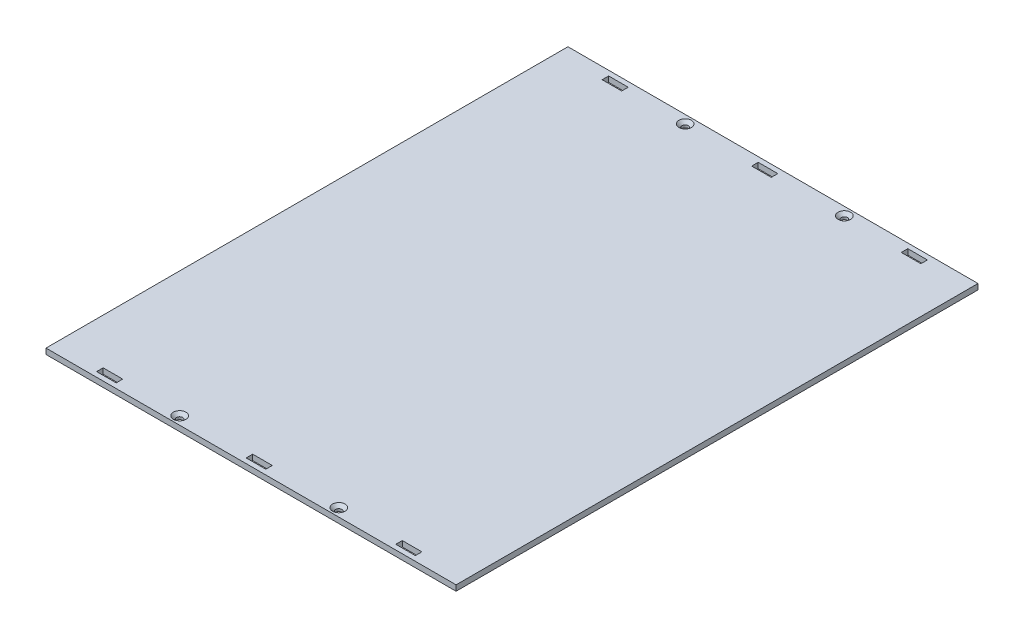
SolidWorks part; units mm, degrees
ref_plane "Alzado" through (0, 0, 0) normal (0, 0, 1) x (1, 0, 0)
ref_plane "Planta" through (0, 0, 0) normal (0, 1, 0) x (1, 0, 0)
ref_plane "Vista lateral" through (0, 0, 0) normal (1, 0, 0) x (0, 0, -1)
sketch "Croquis1" plane through (0, 0, 0) normal (0, 1, 0) x (1, 0, 0)
  line L0 (0, 0) -> (0, -140) construction
  line L1 (110, -140) -> (-110, -140)
  line L2 (110, -140) -> (110, 140)
  line L3 (110, 140) -> (-110, 140)
  line L4 (-110, -140) -> (-110, 140)
  line L5 (110, -140) -> (-110, 140) construction
  line L6 (110, 140) -> (-110, -140) construction
  line L7 (-85.5, -133.85) -> (-75, -133.85)
  line L8 (-5.25, -137.35) -> (5.25, -137.35)
  line L9 (-5.25, -137.35) -> (-5.25, -133.85)
  line L10 (-5.25, -133.85) -> (5.25, -133.85)
  line L11 (5.25, -137.35) -> (5.25, -133.85)
  line L12 (-5.25, -137.35) -> (5.25, -133.85) construction
  line L13 (-5.25, -133.85) -> (5.25, -137.35) construction
  line L14 (-85.5, -137.35) -> (-85.5, -133.85)
  line L15 (-85.5, -137.35) -> (-75, -137.35)
  line L16 (-75, -137.35) -> (-75, -133.85)
  line L17 (-5.25, -133.85) -> (-85.5, -133.85) construction
  line L18 (85.5, -137.35) -> (85.5, -133.85)
  line L19 (85.5, -137.35) -> (75, -137.35)
  line L20 (75, -137.35) -> (75, -133.85)
  line L21 (85.5, -133.85) -> (75, -133.85)
  line L22 (0, 0) -> (-110, 0) construction
  line L23 (-5.25, 137.35) -> (-5.25, 133.85)
  line L24 (-5.25, 133.85) -> (5.25, 133.85)
  line L25 (5.25, 137.35) -> (5.25, 133.85)
  line L26 (-5.25, 137.35) -> (5.25, 137.35)
  line L27 (85.5, 137.35) -> (75, 137.35)
  line L28 (75, 137.35) -> (75, 133.85)
  line L29 (85.5, 133.85) -> (75, 133.85)
  line L30 (85.5, 137.35) -> (85.5, 133.85)
  line L31 (-85.5, 137.35) -> (-85.5, 133.85)
  line L32 (-85.5, 137.35) -> (-75, 137.35)
  line L33 (-75, 137.35) -> (-75, 133.85)
  line L34 (-85.5, 133.85) -> (-75, 133.85)
  line L35 (-75, -135.6) -> (-71.6859, -135.6) construction
  circle A5 centre (-42.7, -135.6) radius 1
  circle A6 centre (42.7, -135.6) radius 1
  circle A7 centre (42.7, 135.6) radius 1
  circle A8 centre (-42.7, 135.6) radius 1
  point P0 (0, 0)
  point P8 (0, -135.6)
  point P21 (0, 0)
  point P22 (0, 0)
  dimension "D8" = 32.3
  dimension "D9" = 2
  dimension "D1" = 220
  dimension "D2" = 280
  dimension "D3" = 10.5
  dimension "D4" = 3.5
  dimension "D5" = 2.65
  dimension "D7" = 75
  dimension "D6" = 2
extrude "Saliente-Extruir1" add sketch "Croquis1" along normal blind 3
hole_wizard "Refrentado para tornillo tapón con cabeza plana de clavija de M31" positions "Croquis3D1" profile "Croquis2" countersink size "M3" standard "Ansi Metric" end condition through all
sketch3d "Croquis3D1"
  line L0 (-42.7, 3, 135.6) -> (-42.7, 0, 135.6) construction
  line L1 (42.7, 3, 135.6) -> (42.7, 0, 135.6) construction
  line L2 (-42.7, 3, -135.6) -> (-42.7, 0, -135.6) construction
  line L3 (42.7, 3, -135.6) -> (42.7, 0, -135.6) construction
  point P0 (-42.7, 3, 135.6)
  point P4 (42.7, 3, 135.6)
  point P8 (-42.7, 3, -135.6)
  point P12 (42.7, 3, -135.6)
sketch "Croquis2" plane through (-42.7, 3, 135.6) normal (1, 0, 0) x (0, 0, 1)
  line L0 (0, 0) -> (0, 3)
  line L1 (0, 3) -> (1.7, 3)
  line L2 (1.7, 3) -> (1.7, 1.66)
  line L3 (1.7, 1.66) -> (3.36, 0)
  line L5 (3.36, 0) -> (0, 0)
  line L6 (-1.7, 1.66) -> (-3.36, 0) construction
  line L11 (0, -6.35) -> (0, 107.95) construction
  dimension "Diámetro de taladro hasta el siguiente" = 3.4
  dimension "Profundidad de taladro hasta el siguiente" = 3
  dimension "Diámetro de avellanado cercano" = 6.72
  dimension "Ángulo de avellanado cercano" = 90
